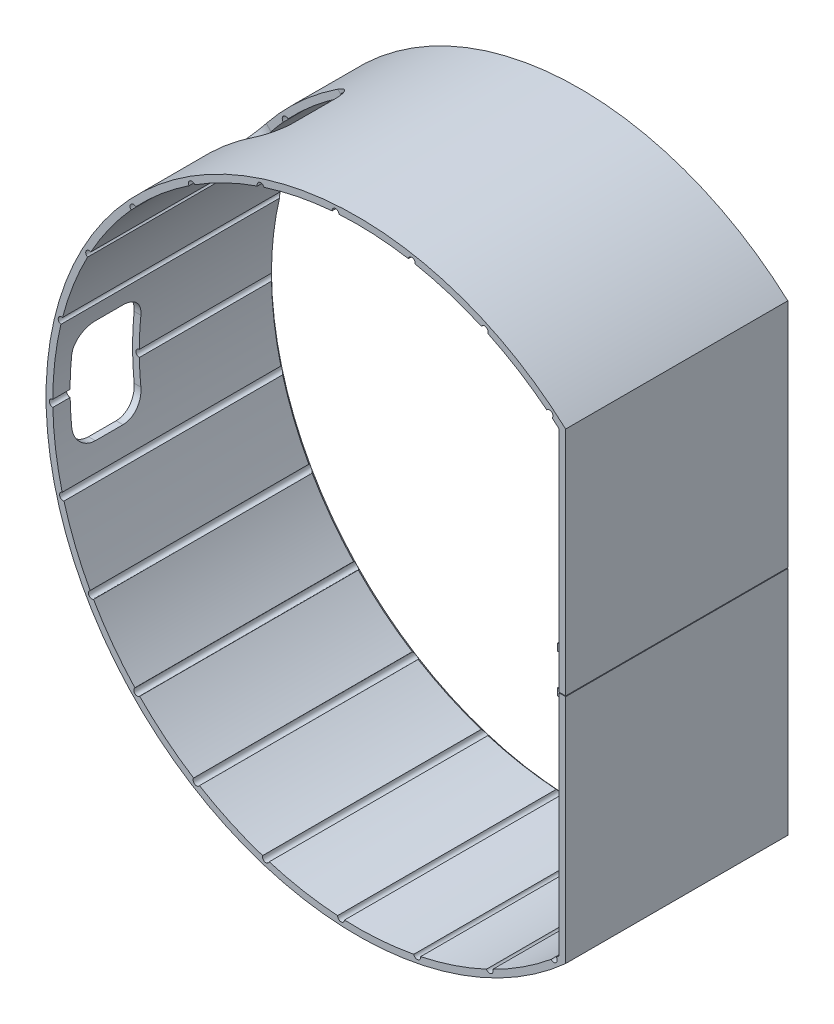
SolidWorks part; units mm, degrees
ref_plane "Front Plane" through (0, 0, 0) normal (1, 0, 0) x (0, 1, 0)
ref_plane "Top Plane" through (0, 0, 0) normal (0, 0, 1) x (0, 1, 0)
ref_plane "Right Plane" through (0, 0, 0) normal (0, 1, 0) x (-1, 0, 0)
sketch "Sketch1" plane through (0, 0, 0) normal (0, 0, 1) x (0, 1, 0)
  line L0 (-66.9026, -60.2) -> (-0.1, -60.2)
  line L1 (-65.9842, -58.3) -> (-0.1, -58.3)
  line L2 (-0.1, -60.2) -> (-0.1, -58.3)
  line L3 (0.1, -60.2) -> (0.1, -58.3)
  line L4 (0.1, -60.2) -> (66.9026, -60.2)
  line L5 (0.1, -58.3) -> (65.9842, -58.3)
  arc A0 (66.9026, -60.2) -> (-66.9026, -60.2) centre (0, 0) ccw
  arc A1 (65.9842, -58.3) -> (-65.9842, -58.3) centre (0, 0) ccw
  dimension "D1" = 180
  dimension "D2" = 176.1
  dimension "D3" = 60.2
  dimension "D4" = 1.9
  dimension "D5" = 0.1
  dimension "D6" = 0.1
extrude "Boss-Extrude1" add sketch "Sketch1" along normal blind 64.2
sketch "Sketch2" plane through (0, 0, 0) normal (1, 0, 0) x (0, 1, 0)
  line L0 (0, 67.3305) -> (0, -7.6543) construction
ref_plane "Plane1" through (0, 0, 0) normal (0.7071, -0.7071, 0) x (0, 0, -1)
sketch "Sketch3" plane through (0, 0, 0) normal (0.7071, -0.7071, 0) x (0, 0, -1)
  line L0 (-64.2, 87.8822) -> (-64.2, -88.05) construction
  line L1 (-44.2, -16.05) -> (-20.2, -16.05)
  line L2 (-44.2, -16.05) -> (-44.2, 23.95)
  line L3 (-44.2, 23.95) -> (-20.2, 23.95)
  line L4 (-20.2, -16.05) -> (-20.2, 23.95)
  line L6 (-64.2, -88.05) -> (0, -88.05) construction
  dimension "D1" = 40
  dimension "D2" = 24
  dimension "D3" = 20
  dimension "D4" = 72
extrude "Cut-Extrude1" cut sketch "Sketch3" against normal blind 120.2
sketch "Sketch4" plane through (0, 0, 0) normal (1, 0, 0) x (0, 1, 0)
  line L0 (0, 200067.3305) -> (0, -200007.6543) construction
  line L1 (-15, 59.2) -> (15, 59.2)
  line L2 (-15, 59.2) -> (-15, 39.2)
  line L3 (-15, 39.2) -> (15, 39.2)
  line L4 (15, 59.2) -> (15, 39.2)
  line L5 (90, 64.2) -> (-90, 64.2) construction
  dimension "D1" = 15
  dimension "D2" = 15
  dimension "D3" = 20
  dimension "D4" = 5
extrude "Cut-Extrude2" cut sketch "Sketch4" against normal blind 120.2
fillet "Fillet1" radius 6 8 edges at (-43.6939, 77.5643, 44.2) (-73.2676, 50.5695, 44.2) (-73.2676, 50.5695, 20.2) (-43.6939, 77.5643, 20.2) (-87.7521, 15, 39.2) (-87.7521, -15, 39.2) (-87.7521, -15, 59.2) (-87.7521, 15, 59.2)
sketch "Sketch5" plane through (58.3, 0, 0) normal (-1, 0, 0) x (0, -1, 0)
  line L0 (90, 64.2) -> (-90, 64.2) construction
  line L5 (-6.5842, 58.7) -> (-4.5842, 58.7)
  line L6 (-6.5842, 58.7) -> (-6.5842, 49.7)
  line L7 (-6.5842, 49.7) -> (-4.5842, 49.7)
  line L8 (-4.5842, 58.7) -> (-4.5842, 49.7)
  line L9 (-6.5842, 58.7) -> (-4.5842, 49.7) construction
  line L10 (-6.5842, 49.7) -> (-4.5842, 58.7) construction
  line L11 (-65.9842, 64.2) -> (-65.9842, 0) construction
  line L12 (-65.9842, 32.1) -> (65.9842, 32.1) construction
  line L13 (65.9842, 64.2) -> (65.9842, 0) construction
  point P0 (-5.5842, 54.2)
  dimension "D1" = 2
  dimension "D2" = 9
  dimension "D3" = 10
  dimension "D4" = 60.4
extrude "Boss-Extrude2" add sketch "Sketch5" along normal blind 6
sketch "Sketch6" plane through (0, 0, 58.7) normal (0, 0, 1) x (1, 0, 0)
  line L0 (58.3, 6.5842) -> (56.1, 6.5842) construction
  line L1 (52.3, 6.5842) -> (58.3, 6.5842) construction
  line L2 (56.1, 6.5842) -> (56.1, 7.7842)
  line L3 (52.3, 6.5842) -> (56.1, 7.7842)
  line L4 (52.3, 6.5842) -> (56.1, 6.5842)
  dimension "D1" = 1.2
extrude "Boss-Extrude3" add sketch "Sketch6" against normal blind 9
sketch "Sketch8" plane through (58.3, 0, 0) normal (-1, 0, 0) x (0, -1, 0)
  line L0 (0, 74.2736) -> (0, -25.5173) construction
  line L1 (0, 200067.3305) -> (0, -200007.6543) construction
  line L2 (-65.9842, 32.1) -> (101.8942, 32.1) construction
  line L3 (-65.9842, 64.2) -> (-65.9842, 0) construction
ref_plane "Plane2" through (0, 0, 0) normal (0, 1, 0) x (-1, 0, 0)
ref_plane "Plane3" through (0, 0, 32.1) normal (0, 0, 1) x (0, -1, 0)
chamfer "Chamfer1" distance 1 angle 45 3 edges at (-88.05, 0, 0) (58.3, 33.0421, 0) (58.3, -33.0421, 0)
sketch "Sketch9" plane through (0, 0, 64.2) normal (0, 0, 1) x (1, 0, 0)
  circle A0 centre (-88.0464, -0.7976) radius 1
  arc A1 (58.3, 65.9842) -> (58.3, -65.9842) centre (0, 0) ccw construction
  circle A31 centre (-85.4786, 21.1237) radius 1
  circle A32 centre (-77.5399, 41.7177) radius 1
  circle A33 centre (-64.7291, 59.6905) radius 1
  circle A34 centre (-47.8511, 73.9126) radius 1
  circle A35 centre (-27.9664, 83.4906) radius 1
  circle A36 centre (-6.3245, 87.8226) radius 1
  circle A37 centre (15.7148, 86.6363) radius 1
  circle A38 centre (36.7666, 80.0064) radius 1
  circle A39 centre (55.5083, 68.3493) radius 1
  circle A46 centre (56.7374, -67.3325) radius 1
  circle A47 centre (38.21, -79.3272) radius 1
  circle A48 centre (17.2817, -86.3374) radius 1
  circle A49 centre (-4.7325, -87.9227) radius 1
  circle A50 centre (-26.4493, -83.9836) radius 1
  circle A51 centre (-46.5042, -74.7674) radius 1
  circle A52 centre (-63.6371, -60.8533) radius 1
  circle A53 centre (-76.7714, -43.1156) radius 1
  circle A54 centre (-85.0819, -22.6688) radius 1
  circle A55 centre (70.7622, 52.3976) radius 1 [skipped]
  circle A56 centre (81.5698, 33.1536) radius 1 [skipped]
  circle A57 centre (87.2521, 11.8265) radius 1 [skipped]
  circle A58 centre (87.4521, -10.2438) radius 1 [skipped]
  circle A59 centre (82.1571, -31.6704) radius 1 [skipped]
  circle A60 centre (71.6998, -51.1071) radius 1 [skipped]
  point P56 (0, 0)
  point P66 (0, 0)
  dimension "D1" = 2
  dimension "D2" = 25
extrude "Cut-Extrude5" cut sketch "Sketch9" against normal blind 100
mirror "Mirror1" about plane through (0, 0, 0) normal (0, 1, 0) of "Boss-Extrude2", "Boss-Extrude3"
mirror "Mirror2" about plane through (0, 0, 32.1) normal (0, 0, 1) of "Mirror1", "Boss-Extrude2", "Boss-Extrude3"
